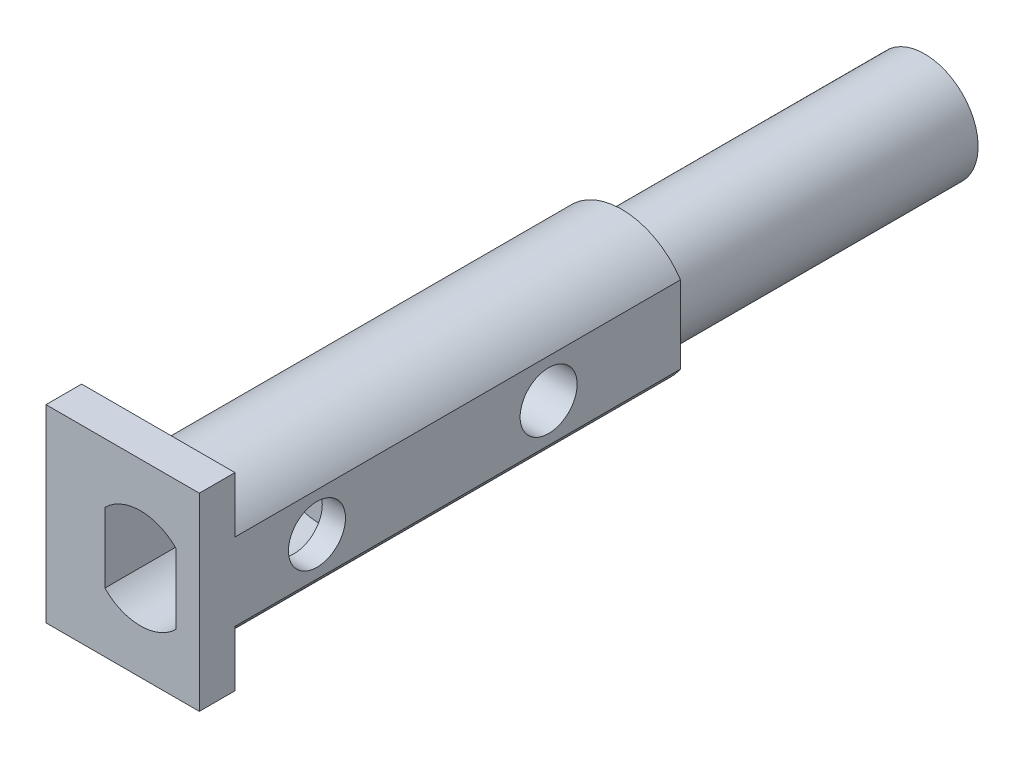
SolidWorks part; units mm, degrees
ref_plane "Ön Düzlem" through (0, 0, 0) normal (0, 0, 1) x (1, 0, 0)
ref_plane "Üst Düzlem" through (0, 0, 0) normal (0, 1, 0) x (1, 0, 0)
ref_plane "Sağ Düzlem" through (0, 0, 0) normal (1, 0, 0) x (0, 0, -1)
sketch "Çizim1" plane through (0, 0, 0) normal (0, 0, 1) x (1, 0, 0)
  line L1 (5.3033, -5.3033) -> (-5.3033, -5.3033)
  line L2 (5.3033, -5.3033) -> (5.3033, 5.3033)
  line L3 (5.3033, 5.3033) -> (-5.3033, 5.3033)
  line L4 (-5.3033, -5.3033) -> (-5.3033, 5.3033)
  line L5 (5.3033, -5.3033) -> (-5.3033, 5.3033) construction
  line L6 (5.3033, 5.3033) -> (-5.3033, -5.3033) construction
  circle A0 centre (0, 0) radius 7.5 construction
  dimension "D1" = 15
extrude "Yükseklik-Ekstrüzyon1" add sketch "Çizim1" along normal blind 2
sketch "Çizim2" plane through (0, 0, 0) normal (0, 0, -1) x (-1, 0, 0)
  circle A0 centre (0, 0) radius 3.95
  dimension "D1" = 7.9
extrude "Yükseklik-Ekstrüzyon2" add sketch "Çizim2" along normal blind 25 contours A0
sketch "Çizim3" plane through (0, 0, 2) normal (0, 0, 1) x (1, 0, 0)
  line L0 (-2, -1.9596) -> (-2, 1.9596)
  line L1 (2, -1.9596) -> (2, 1.9596)
  arc A0 (-2, -1.9596) -> (2, -1.9596) centre (0, 0) ccw
  arc A1 (2, 1.9596) -> (-2, 1.9596) centre (0, 0) ccw
  dimension "D1" = 5.6
  dimension "D2" = 2
  dimension "D3" = 2
extrude "Kes-Ekstrüzyon1" cut sketch "Çizim3" against normal blind 10
sketch "Çizim5" plane through (0, 0, 0) normal (1, 0, 0) x (0, 0, -1)
  line L0 (25, -3.95) -> (25, 3.95) construction
  circle A0 centre (4.6, 0) radius 1.6
  circle A1 centre (17.6, 0) radius 1.6
  point P4 (-0.4, 0)
  point P7 (-0.4, 0)
  point P8 (0, 0)
  dimension "D3" = 3.2
  dimension "D1" = 7.4
  dimension "D2" = 13
extrude "Kes-Ekstrüzyon3" cut sketch "Çizim5" against normal mid plane 52
sketch "Çizim8" plane through (0, 0, -25) normal (0, 0, -1) x (-1, 0, 0)
  line L0 (-3.3, 6.8105) -> (-3.3, -6.8105)
  line L1 (-3.3, 6.8105) -> (-8.3, 6.8105)
  line L2 (-8.3, 6.8105) -> (-8.3, -6.8105)
  line L3 (-8.3, -6.8105) -> (-3.3, -6.8105)
  circle A0 centre (0, 0) radius 3.95 construction
  point P2 (-3.3, 0)
  dimension "D1" = 5
  dimension "D2" = 3.3
  dimension "D3" = 6.8105
extrude "Kes-Ekstrüzyon4" cut sketch "Çizim8" against normal through all
ref_plane "Plane1" through (0, 0, -9) normal (0, 0, 1) x (1, 0, 0)
ref_plane "Plane2" through (0, 0, -25) normal (0, 0, 1) x (1, 0, 0)
ref_plane "Plane3" through (0, 0, -42) normal (0, 0, 1) x (1, 0, 0)
sketch "Sketch2" plane through (0, 0, -25) normal (0, 0, -1) x (-1, 0, 0)
  circle A0 centre (0, 0) radius 3
  dimension "D1" = 6
extrude "Boss-Extrude1" add sketch "Sketch2" along normal blind 17
